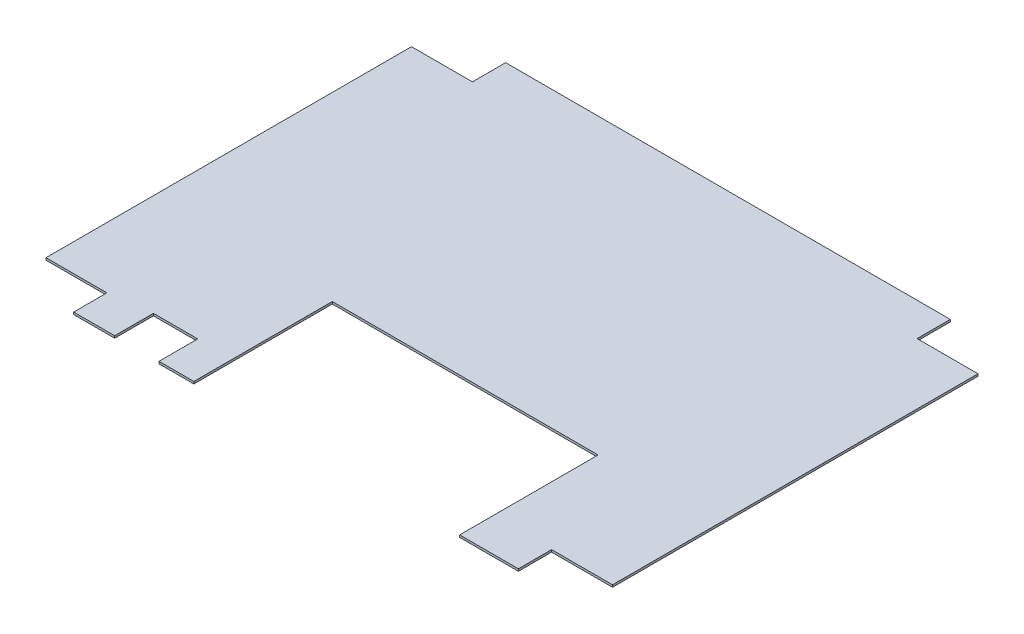
SolidWorks part; units mm, degrees
ref_plane "Alzado" through (0, 0, 0) normal (0, 0, 1) x (1, 0, 0)
ref_plane "Planta" through (0, 0, 0) normal (0, 1, 0) x (1, 0, 0)
ref_plane "Vista lateral" through (0, 0, 0) normal (1, 0, 0) x (0, 0, -1)
sketch "Croquis1" plane through (0, 0, 0) normal (0, 1, 0) x (1, 0, 0)
  line L1 (0, 0) -> (511.5, 0)
  line L2 (0, 0) -> (0, 390)
  line L3 (0, 390) -> (511.5, 390)
  line L4 (511.5, 0) -> (511.5, 390)
  dimension "D1" = 390
  dimension "D2" = 511.5
extrude "Saliente-Extruir1" add sketch "Croquis1" along normal blind 2
sketch "Croquis3" plane through (0, 2, 0) normal (0, 1, 0) x (1, 0, 0)
  line L0 (255.75, 390) -> (255.75, 0) construction
  line L1 (511.5, 0) -> (456.5, 0)
  line L2 (511.5, 0) -> (511.5, 30)
  line L3 (511.5, 30) -> (456.5, 30)
  line L4 (456.5, 0) -> (456.5, 30)
  line L5 (511.5, 390) -> (0, 390) construction
  line L6 (0, 0) -> (511.5, 0) construction
  line L7 (0, 30) -> (55, 30)
  line L8 (511.5, 390) -> (456.5, 390)
  line L9 (511.5, 390) -> (511.5, 360)
  line L10 (511.5, 360) -> (456.5, 360)
  line L11 (456.5, 390) -> (456.5, 360)
  line L12 (55, 0) -> (55, 30)
  line L13 (0, 0) -> (55, 0)
  line L14 (0, 0) -> (0, 30)
  line L15 (0, 360) -> (55, 360)
  line L16 (55, 390) -> (55, 360)
  line L17 (0, 390) -> (55, 390)
  line L18 (0, 390) -> (0, 360)
  dimension "D1" = 30
  dimension "D2" = 55
  dimension "D3" = 30
  dimension "D4" = 55
extrude "Cortar-Extruir1" cut sketch "Croquis3" against normal up to surface (2 mm away) up to face at (255.75, 0, -195)
sketch "Croquis4" plane through (0, 2, 0) normal (0, 1, 0) x (1, 0, 0)
  line L0 (55, 0) -> (456.5, 0) construction
  line L1 (403.5, 0) -> (163.5, 0)
  line L2 (403.5, 0) -> (403.5, 125)
  line L3 (403.5, 125) -> (163.5, 125)
  line L4 (163.5, 0) -> (163.5, 125)
  line L5 (511.5, 30) -> (511.5, 360) construction
  dimension "D1" = 240
  dimension "D2" = 125
  dimension "D3" = 108
extrude "Cortar-Extruir2" cut sketch "Croquis4" against normal up to surface (2 mm away) up to face at (255.75, 0, -195)
sketch "Croquis5" plane through (0, 2, 0) normal (0, 1, 0) x (1, 0, 0)
  line L0 (55, 0) -> (163.5, 0) construction
  line L1 (92, 0) -> (132, 0)
  line L2 (92, 0) -> (92, 35)
  line L3 (92, 35) -> (132, 35)
  line L4 (132, 0) -> (132, 35)
  line L6 (55, 0) -> (55, 30) construction
  dimension "D1" = 40
  dimension "D2" = 37
  dimension "D3" = 35
extrude "Cortar-Extruir3" cut sketch "Croquis5" against normal up to surface (2 mm away) up to face at (262.6875, 0, -161.875)
